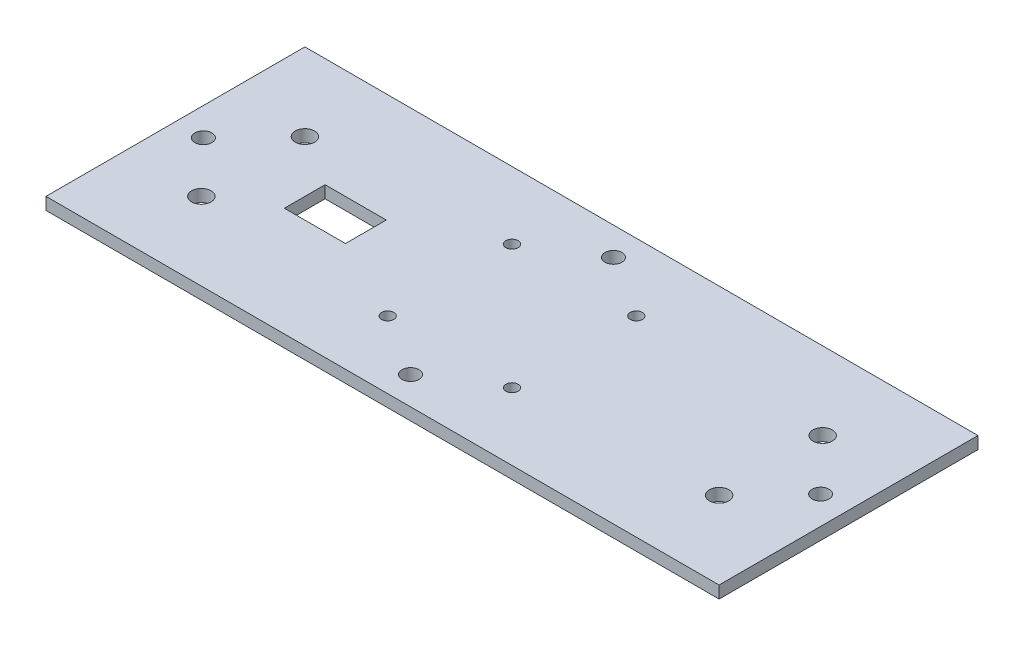
SolidWorks part; units mm, degrees
material "Thornel VCB-20 Carbon Cloth"
ref_plane "Front Plane" through (0, 0, 0) normal (0, 0, 1) x (1, 0, 0)
ref_plane "Top Plane" through (0, 0, 0) normal (0, 1, 0) x (1, 0, 0)
ref_plane "Right Plane" through (0, 0, 0) normal (1, 0, 0) x (0, 0, -1)
sketch "Sketch1" plane through (0, 0, 0) normal (0, 1, 0) x (1, 0, 0)
  line L0 (82.55, -31.75) -> (82.55, 31.75)
  line L1 (82.55, -31.75) -> (-82.55, -31.75)
  line L2 (82.55, 31.75) -> (-82.55, 31.75)
  line L3 (-82.55, -31.75) -> (-82.55, 31.75)
  line L4 (82.55, -31.75) -> (-82.55, 31.75) construction
  line L5 (82.55, 31.75) -> (-82.55, -31.75) construction
  point P1 (0, 0)
  dimension "D1" = 165.1
  dimension "D2" = 63.5
extrude "Boss-Extrude1" add sketch "Sketch1" along normal blind 3
sketch "Sketch6" plane through (0, 0, 0) normal (0, -1, 0) x (1, 0, 0)
  line L0 (-82.55, -31.75) -> (-82.55, 31.75) construction
  line L1 (-50.8, 5.047) -> (-35.8, 5.047)
  line L2 (-50.8, 5.047) -> (-50.8, -4.953)
  line L3 (-50.8, -4.953) -> (-35.8, -4.953)
  line L4 (-35.8, 5.047) -> (-35.8, -4.953)
  line L6 (82.55, -31.75) -> (-82.55, -31.75) construction
  circle A0 centre (-15.25, 15.25) radius 1.5
  circle A1 centre (15.25, 15.25) radius 1.5
  circle A2 centre (-15.25, -15.25) radius 1.5
  circle A3 centre (15.25, -15.25) radius 1.5
  dimension "D5" = 3
  dimension "D6" = 3
  dimension "D7" = 3
  dimension "D8" = 3
  dimension "D1" = 15
  dimension "D2" = 10
  dimension "D3" = 31.75
  dimension "D4" = 26.797
  dimension "D9" = 15.25
  dimension "D10" = 15.25
  dimension "D11" = 15.25
  dimension "D12" = 15.25
  dimension "D13" = 15.25
  dimension "D14" = 15.25
  dimension "D15" = 15.25
  dimension "D16" = 15.25
extrude "Cut-Extrude1" cut sketch "Sketch6" against normal up to next
sketch "Sketch7" plane through (0, 3, 0) normal (0, 1, 0) x (1, 0, 0)
  line L0 (-82.55, 31.75) -> (-82.55, -31.75) construction
  line L1 (82.55, -31.75) -> (82.55, 31.75) construction
  line L2 (-82.55, -31.75) -> (82.55, -31.75) construction
  line L3 (82.55, 31.75) -> (-82.55, 31.75) construction
  circle A0 centre (-77.47, 26.67) radius 1.5
  circle A1 centre (-77.47, -26.67) radius 1.5
  circle A2 centre (77.47, -26.67) radius 1.5
  circle A3 centre (77.47, 26.67) radius 1.5
  dimension "D9" = 3
  dimension "D10" = 3
  dimension "D11" = 3
  dimension "D12" = 3
  dimension "D1" = 5.08
  dimension "D2" = 5.08
  dimension "D3" = 5.08
  dimension "D4" = 5.08
  dimension "D5" = 5.08
  dimension "D6" = 5.08
  dimension "D7" = 5.08
  dimension "D8" = 5.08
sketch "Sketch8" plane through (0, 3, 0) normal (0, 1, 0) x (1, 0, 0)
  line L0 (-82.55, -31.75) -> (82.55, -31.75) construction
  line L1 (-82.55, 31.75) -> (-82.55, -31.75) construction
  line L2 (82.55, -31.75) -> (82.55, 31.75) construction
  line L3 (82.55, 31.75) -> (-82.55, 31.75) construction
  circle A0 centre (-63.5, -12.7) radius 2.3813
  circle A1 centre (-63.5, 12.7) radius 2.3813
  circle A2 centre (63.5, 12.7) radius 2.3813
  circle A3 centre (63.5, -12.7) radius 2.3813
  dimension "D1" = 4.7625
  dimension "D4" = 4.7625
  dimension "D5" = 4.7625
  dimension "D6" = 4.7625
  dimension "D2" = 19.05
  dimension "D3" = 19.05
  dimension "D7" = 19.05
  dimension "D8" = 19.05
  dimension "D9" = 19.05
  dimension "D10" = 19.05
  dimension "D11" = 19.05
  dimension "D12" = 19.05
extrude "Cut-Extrude3" cut sketch "Sketch8" against normal up to next
sketch "Sketch9" plane through (0, 3, 0) normal (0, 1, 0) x (1, 0, 0)
  line L0 (-82.55, 31.75) -> (-82.55, -31.75) construction
  line L1 (82.55, -31.75) -> (82.55, 31.75) construction
  circle A0 centre (-75.692, 0) radius 2.0828
  circle A1 centre (75.692, 0) radius 2.0828
  dimension "D1" = 6.858
  dimension "D2" = 6.858
extrude "Cut-Extrude5" cut sketch "Sketch9" against normal blind 5.08
sketch "Sketch10" plane through (0, 3, 0) normal (0, 1, 0) x (1, 0, 0)
  line L0 (-82.55, -31.75) -> (82.55, -31.75) construction
  line L1 (82.55, 31.75) -> (-82.55, 31.75) construction
  circle A0 centre (0, -24.892) radius 2.0828
  circle A1 centre (0, 24.892) radius 2.0828
  dimension "D1" = 6.858
  dimension "D2" = 6.858
extrude "Cut-Extrude6" cut sketch "Sketch10" against normal blind 5.08 contours A1 | A0
